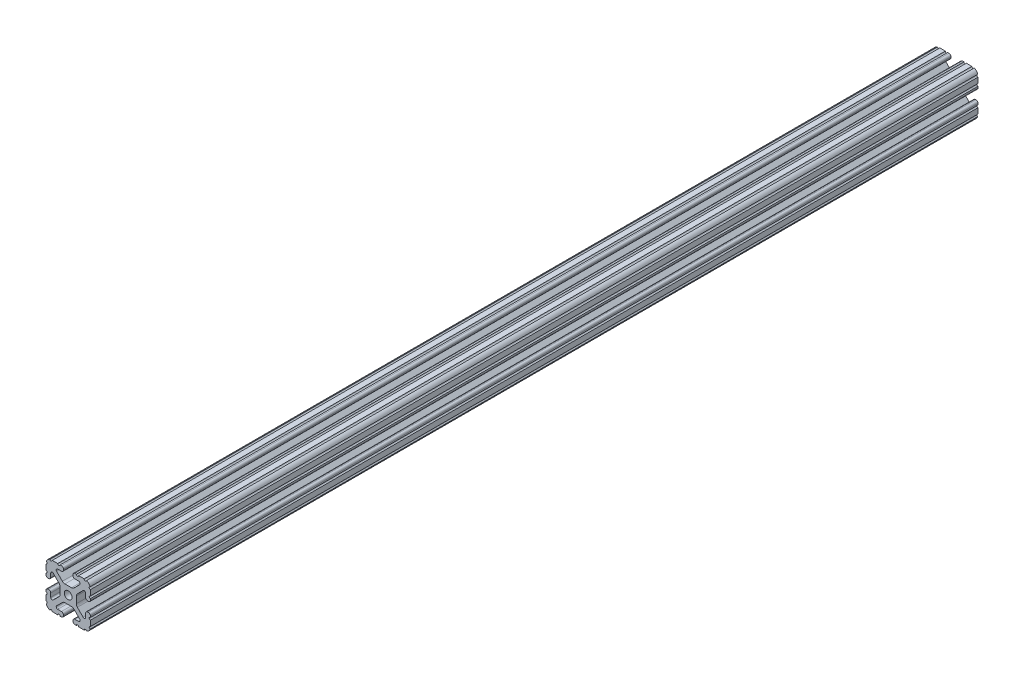
SolidWorks part; units mm, degrees
ref_plane "Front Plane" through (0, 0, 0) normal (0, 0, 1) x (1, 0, 0)
ref_plane "Top Plane" through (0, 0, 0) normal (0, 1, 0) x (1, 0, 0)
ref_plane "Right Plane" through (0, 0, 0) normal (1, 0, 0) x (0, 0, -1)
sketch "Sketch2" plane through (0, 0, 0) normal (0, 0, 1) x (1, 0, 0)
  line L0 (0, 19.05) -> (0, -19.05) construction
  line L1 (-19.05, 0) -> (19.05, 0) construction
  line L2 (4.064, -19.05) -> (19.05, -19.05)
  line L3 (19.05, -19.05) -> (19.05, -4.064)
  line L4 (4.064, -19.05) -> (4.064, -14.986)
  line L5 (4.064, -14.986) -> (12.1123, -14.986)
  line L6 (12.1123, -14.986) -> (4.1113, -6.985)
  line L7 (0, 0) -> (19.05, -19.05) construction
  line L8 (19.05, -4.064) -> (14.986, -4.064)
  line L9 (14.986, -4.064) -> (14.986, -12.1123)
  line L10 (14.986, -12.1123) -> (6.985, -4.1113)
  circle A0 centre (0, 0) radius 3.3274
  arc A1 (8.9963, -14.986) -> (9.909, -12.7826) centre (8.9963, -13.6953) ccw construction
  point P8 (0, -6.985)
  dimension "Center Hole Diameter" = 6.6548
  dimension "Rail Height" = 38.1
  dimension "Rail Width" = 38.1
  dimension "T-Slot Width" = 8.128
  dimension "Slot Inner Width" = 20.574
  dimension "Thickness" = 4.064
  dimension "Slot Depth" = 8.001
  dimension "D1" = 4.064
sketch "Sketch3" plane through (0, 0, 0) normal (1, 0, 0) x (0, 0, -1)
  line L0 (-381, -19.05) -> (381, -19.05) construction
  line L1 (-355.6, 0) -> (355.6, 0) construction
  dimension "Length" = 762
  dimension "D1" = 25.4
sketch "Sketch4" plane through (0, 0, 0) normal (0, 0, 1) x (1, 0, 0)
  line L0 (5.7912, -19.05) -> (14.3002, -19.05)
  line L1 (4.064, -19.05) -> (19.05, -19.05) construction
  line L2 (4.064, -19.05) -> (4.064, -14.986) construction
  line L3 (4.064, -14.986) -> (12.1123, -14.986) construction
  line L4 (4.064, -16.7132) -> (4.064, -17.3228)
  line L5 (5.7912, -14.986) -> (8.9963, -14.986)
  line L6 (0, -6.985) -> (2.833, -6.985)
  line L7 (12.1123, -14.986) -> (4.1113, -6.985) construction
  line L8 (5.0152, -7.8889) -> (9.909, -12.7826)
  line L9 (19.05, -19.05) -> (19.05, -4.064) construction
  line L10 (14.986, -12.1123) -> (6.985, -4.1113) construction
  line L11 (14.986, -4.064) -> (14.986, -12.1123) construction
  line L12 (14.986, -8.9963) -> (14.986, -5.7912)
  line L13 (19.05, -4.064) -> (14.986, -4.064) construction
  line L14 (16.7132, -4.064) -> (17.3228, -4.064)
  line L15 (19.05, -5.7912) -> (19.05, -14.3002)
  line L16 (12.7826, -9.909) -> (7.8889, -5.0152)
  line L17 (6.985, 0) -> (6.985, -2.833)
  line L18 (-19.05, 0) -> (19.05, 0) construction
  line L19 (0, -6.985) -> (0, -3.3274)
  line L20 (0, 19.05) -> (0, -19.05) construction
  line L21 (6.985, 0) -> (3.3274, 0)
  arc A0 (4.064, -17.3228) -> (5.7912, -19.05) centre (5.7912, -17.3228) ccw
  arc A2 (4.064, -16.7132) -> (5.7912, -14.986) centre (5.7912, -16.7132) cw
  arc A3 (8.9963, -14.986) -> (9.909, -12.7826) centre (8.9963, -13.6953) ccw
  arc A4 (2.833, -6.985) -> (5.0152, -7.8889) centre (2.833, -10.0711) cw
  arc A5 (14.3002, -19.05) -> (19.05, -14.3002) centre (14.3002, -14.3002) ccw
  arc A6 (12.7826, -9.909) -> (14.986, -8.9963) centre (13.6953, -8.9963) ccw
  arc A7 (14.986, -5.7912) -> (16.7132, -4.064) centre (16.7132, -5.7912) cw
  arc A8 (17.3228, -4.064) -> (19.05, -5.7912) centre (17.3228, -5.7912) cw
  arc A9 (7.8889, -5.0152) -> (6.985, -2.833) centre (10.0711, -2.833) cw
  circle A10 centre (0, 0) radius 3.3274 construction
  arc A11 (0, -3.3274) -> (3.3274, 0) centre (0, 0) ccw
  dimension "D1" = 4.7498
  dimension "D2" = 3.0861
  dimension "D3" = 1.7272
extrude "Boss-Extrude1" add sketch "Sketch4" along normal mid plane 762
sketch "Sketch5" plane through (0, 0, 0) normal (0, 0, 1) x (1, 0, 0)
  line L0 (4.064, -19.05) -> (19.05, -19.05) construction
  line L1 (5.7912, -14.986) -> (8.9963, -14.986) construction
  line L3 (0, 0) -> (19.05, -19.05) construction
  line L4 (8.9963, -14.986) -> (8.9963, -19.05) construction
  line L5 (12.1123, -14.986) -> (4.1113, -6.985) construction
  circle A0 centre (14.7395, -19.05) radius 1.016
  circle A1 centre (7.9803, -19.05) radius 1.016
  circle A2 centre (19.05, -14.7395) radius 1.016
  circle A3 centre (19.05, -7.9803) radius 1.016
  point P10 (7.3938, -14.986)
  point P12 (13.6953, -8.9963)
  dimension "D1" = 2.032
extrude "Cut-Extrude1" cut sketch "Sketch5" against normal through all both and the other way through all
mirror "Mirror1" about plane through (0, 0, 0) normal (1, 0, 0) of bodies 137 134
mirror "Mirror2" about plane through (0, 0, 0) normal (0, 1, 0) of bodies 135
equation "\"D1@Boss-Extrude1\"=\"Length@Sketch3\""
equation "\"D1@Sketch2\"=\"Thickness@Sketch2\""
equation "\"D2@Sketch4\"=\"Slot Inner Width@Sketch2\"*0.15"
equation "\"D1@Sketch4\"=\"D3@Sketch4\"*2.75"
equation "\"D3@Sketch4\"=\"Thickness@Sketch2\"*0.425"
equation "\"D1@Sketch5\"=\"Thickness@Sketch2\"*0.5"
